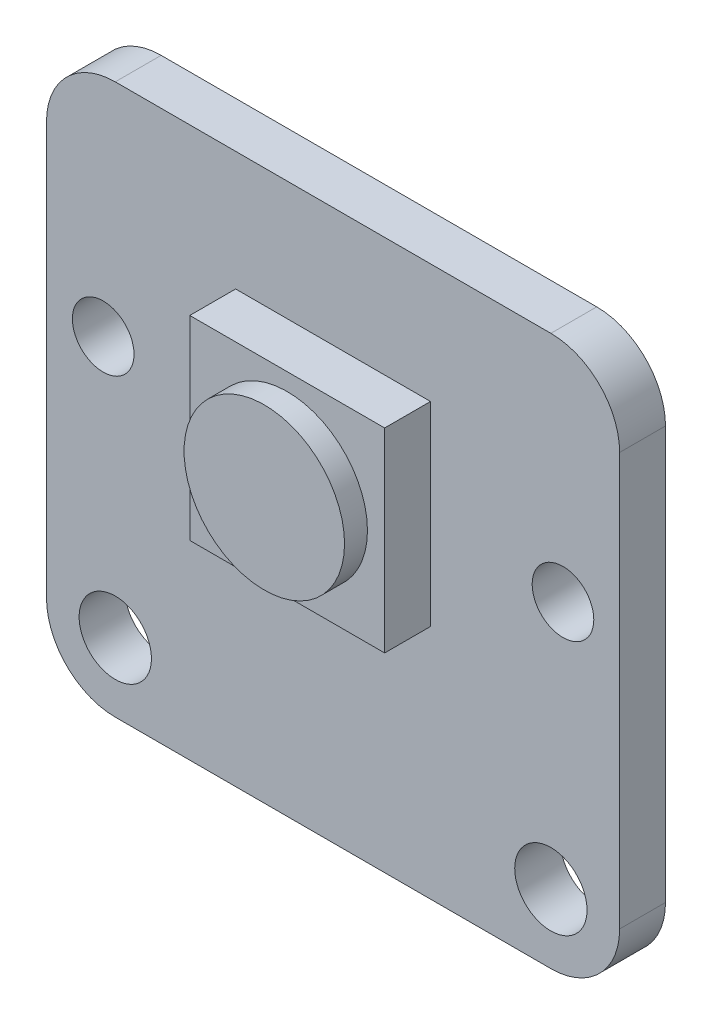
SolidWorks part; units mm, degrees
ref_plane "정면" through (0, 0, 0) normal (0, 0, 1) x (1, 0, 0)
ref_plane "윗면" through (0, 0, 0) normal (0, 1, 0) x (1, 0, 0)
ref_plane "우측면" through (0, 0, 0) normal (1, 0, 0) x (0, 0, -1)
sketch "스케치1" plane through (0, 0, 0) normal (0, 0, 1) x (1, 0, 0)
  line L1 (-12.5, 12) -> (12.5, 12)
  line L2 (-12.5, 12) -> (-12.5, -12)
  line L3 (-12.5, -12) -> (12.5, -12)
  line L4 (12.5, 12) -> (12.5, -12)
  line L5 (-12.5, 12) -> (12.5, -12) construction
  line L6 (-12.5, -12) -> (12.5, 12) construction
  point P0 (0, 0)
  dimension "D1" = 25
  dimension "D2" = 24
extrude "보스-돌출1" add sketch "스케치1" along normal blind 2
sketch "스케치2" plane through (0, 0, 2) normal (0, 0, 1) x (1, 0, 0)
  line L0 (12.5, 12) -> (-12.5, 12) construction
  line L1 (-4.25, 6.8) -> (4.25, 6.8)
  line L2 (-4.25, 6.8) -> (-4.25, -1.7)
  line L3 (-4.25, -1.7) -> (4.25, -1.7)
  line L4 (4.25, 6.8) -> (4.25, -1.7)
  line L5 (-12.5, 12) -> (-12.5, -12) construction
  dimension "D1" = 5.2
  dimension "D2" = 8.25
  dimension "D3" = 8.5
  dimension "D4" = 8.5
extrude "보스-돌출2" add sketch "스케치2" along normal blind 2
sketch "스케치3" plane through (0, 0, 4) normal (0, 0, 1) x (1, 0, 0)
  line L0 (0, 6.8) -> (0, -1.7) construction
  line L1 (4.25, 6.8) -> (-4.25, 6.8) construction
  line L2 (-4.25, -1.7) -> (4.25, -1.7) construction
  circle A0 centre (0, 2.55) radius 3.5
  dimension "D1" = 7
extrude "보스-돌출3" add sketch "스케치3" along normal blind 1
fillet "필렛1" radius 3 1 edges at (-12.5, -12, 1)
fillet "필렛2" radius 3 1 edges at (-12.5, 12, 1)
fillet "필렛3" radius 3 1 edges at (12.5, 12, 1)
fillet "필렛4" radius 3 1 edges at (12.5, -12, 1)
sketch "스케치5" plane through (0, 0, 2) normal (0, 0, 1) x (1, 0, 0)
  line L0 (0, 12) -> (0, -12) construction
  line L1 (9.5, 12) -> (-9.5, 12) construction
  line L2 (-9.5, -12) -> (9.5, -12) construction
  circle A0 centre (-10.0278, 2.1152) radius 1.344
  circle A1 centre (10.0278, 2.1152) radius 1.344
  circle A2 centre (-9.5, -9) radius 1.5772
  circle A3 centre (9.5, -9) radius 1.5772
extrude "컷-돌출1" cut sketch "스케치5" against normal blind 21
